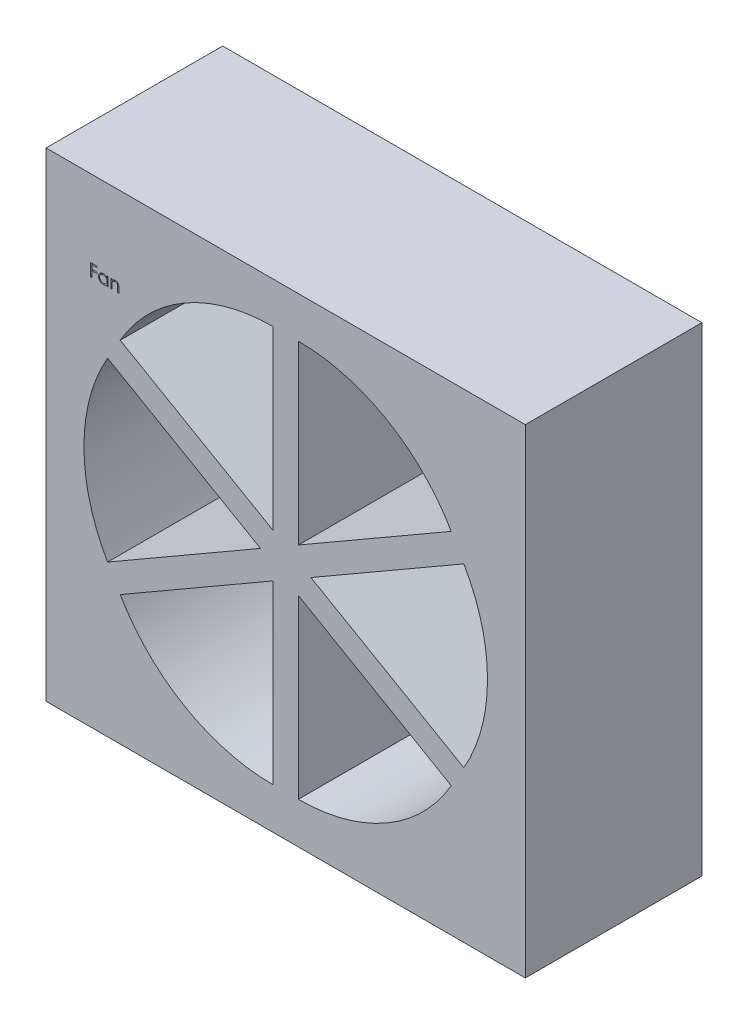
SolidWorks part; units mm, degrees
ref_plane "Front Plane" through (0, 0, 0) normal (0, 0, 1) x (1, 0, 0)
ref_plane "Top Plane" through (0, 0, 0) normal (0, 1, 0) x (1, 0, 0)
ref_plane "Right Plane" through (0, 0, 0) normal (1, 0, 0) x (0, 0, -1)
sketch "Sketch1" plane through (0, 0, 0) normal (0, 0, 1) x (1, 0, 0)
  line L1 (0, 0) -> (120.65, 0)
  line L2 (0, 0) -> (0, 120.65)
  line L3 (0, 120.65) -> (120.65, 120.65)
  line L4 (120.65, 0) -> (120.65, 120.65)
  dimension "D1" = 120.65
  dimension "D2" = 120.65
extrude "Boss-Extrude1" add sketch "Sketch1" along normal blind 44.45
sketch "Sketch2" plane through (0, 0, 44.45) normal (0, 0, 1) x (1, 0, 0)
  text T0 "Fan"
extrude "Cut-Extrude1" cut sketch "Sketch2" against normal blind 3.175
sketch "Sketch3" plane through (0, 0, 44.45) normal (0, 0, 1) x (1, 0, 0)
  line L0 (60.325, 60.325) -> (120.65, 60.325) construction
  line L1 (120.65, 0) -> (120.65, 120.65) construction
  line L2 (60.325, 120.65) -> (60.325, 60.325) construction
  line L3 (120.65, 120.65) -> (0, 120.65) construction
  line L4 (66.675, 60.325) -> (105.1698, 82.55)
  line L6 (66.675, 60.325) -> (105.1698, 38.1)
  line L7 (63.5, 54.8257) -> (101.9948, 32.6007)
  line L8 (63.5, 54.8257) -> (63.5, 10.3757)
  line L9 (57.15, 54.8257) -> (57.15, 10.3757)
  line L10 (57.15, 54.8257) -> (18.6552, 32.6007)
  line L11 (53.975, 60.325) -> (15.4802, 38.1)
  line L12 (53.975, 60.325) -> (15.4802, 82.55)
  line L13 (57.15, 65.8243) -> (18.6552, 88.0493)
  line L14 (57.15, 65.8243) -> (57.15, 110.2743)
  line L15 (63.5, 65.8243) -> (63.5, 110.2743)
  line L16 (63.5, 65.8243) -> (101.9948, 88.0493)
  arc A0 (105.1698, 82.55) -> (105.1698, 38.1) centre (66.675, 60.325) cw
  arc A1 (101.9948, 32.6007) -> (63.5, 10.3757) centre (63.5, 54.8257) cw
  arc A2 (57.15, 10.3757) -> (18.6552, 32.6007) centre (57.15, 54.8257) cw
  arc A3 (15.4802, 38.1) -> (15.4802, 82.55) centre (53.975, 60.325) cw
  arc A4 (18.6552, 88.0493) -> (57.15, 110.2743) centre (57.15, 65.8243) cw
  arc A5 (63.5, 110.2743) -> (101.9948, 88.0493) centre (63.5, 65.8243) cw
  point P28 (60.325, 60.325)
  dimension "D1" = 30
  dimension "D2" = 60
  dimension "D3" = 44.45
  dimension "D4" = 6.35
  dimension "D5" = 6
extrude "Cut-Extrude2" cut sketch "Sketch3" against normal through all
